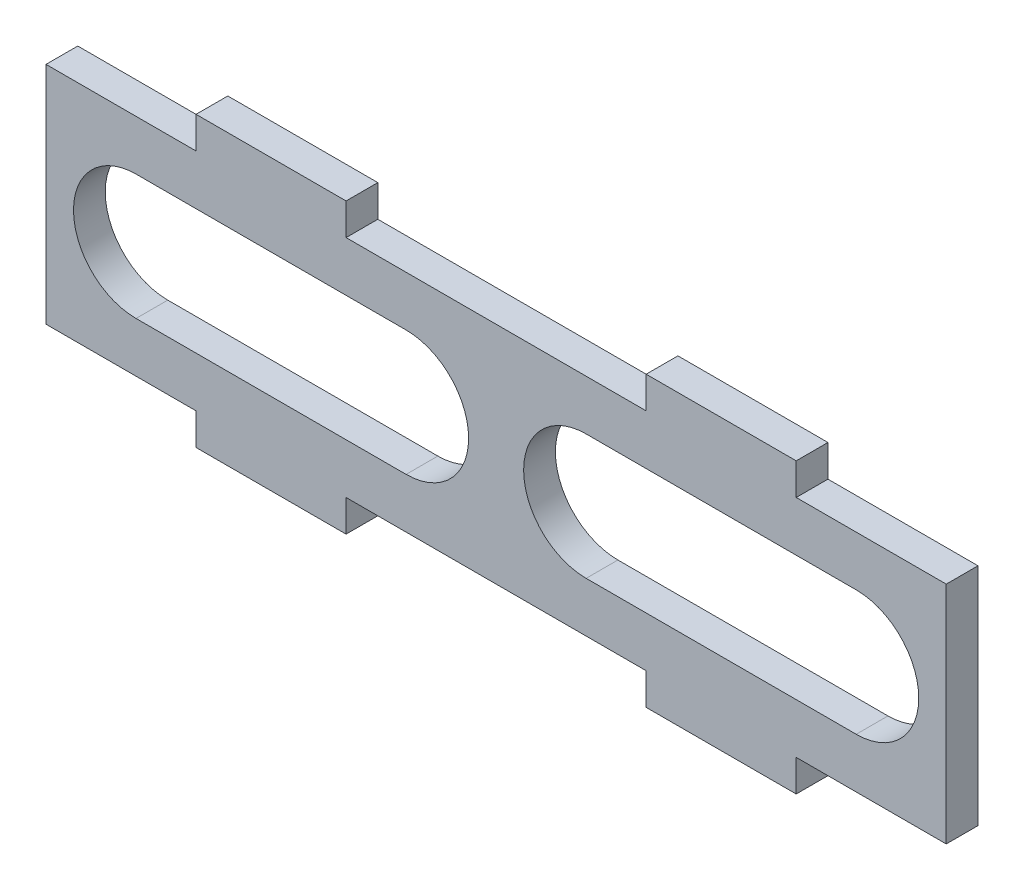
SolidWorks part; units mm, degrees
ref_plane "Plan de face" through (0, 0, 0) normal (0, 0, 1) x (1, 0, 0)
ref_plane "Plan de dessus" through (0, 0, 0) normal (0, 1, 0) x (1, 0, 0)
ref_plane "Plan de droite" through (0, 0, 0) normal (1, 0, 0) x (0, 0, -1)
sketch "Esquisse1" plane through (0, 0, 0) normal (0, 0, 1) x (1, 0, 0)
  line L1 (-90, 0) -> (90, 0)
  line L2 (-90, 0) -> (-90, 45)
  line L3 (-90, 45) -> (90, 45)
  line L4 (90, 0) -> (90, 45)
  point P4 (0, 0)
  dimension "D1" = 45
  dimension "D2" = 180
extrude "Boss.-Extru.1" add sketch "Esquisse1" along normal blind 6.35
sketch "Esquisse2" plane through (0, 0, 6.35) normal (0, 0, 1) x (1, 0, 0)
  line L0 (-90, 22.5) -> (90, 22.5) construction
  line L1 (-90, 45) -> (-90, 0) construction
  line L2 (90, 0) -> (90, 45) construction
  line L3 (-72, 22.5) -> (-18, 22.5) construction
  line L4 (-72, 35) -> (-18, 35)
  line L5 (-72, 10) -> (-18, 10)
  line L6 (0, 22.5) -> (0, 0) construction
  line L7 (0, 0) -> (-90, 0) construction
  line L8 (-45, 0) -> (-45, 22.5) construction
  line L9 (72, 22.5) -> (18, 22.5) construction
  line L10 (72, 35) -> (18, 35)
  line L11 (72, 10) -> (18, 10)
  arc A0 (-72, 35) -> (-72, 10) centre (-72, 22.5) ccw
  arc A1 (-18, 10) -> (-18, 35) centre (-18, 22.5) ccw
  arc A2 (72, 35) -> (72, 10) centre (72, 22.5) cw
  arc A3 (18, 10) -> (18, 35) centre (18, 22.5) cw
  point P8 (-45, 22.5)
  point P22 (45, 22.5)
  dimension "D1" = 18
  dimension "D2" = 25
extrude "Enlèv. mat.-Extru.1" cut sketch "Esquisse2" against normal up to next
sketch "Esquisse3" plane through (0, 0, 6.35) normal (0, 0, 1) x (1, 0, 0)
  line L0 (90, 45) -> (-90, 45) construction
  line L1 (-60, 45) -> (-30, 45)
  line L2 (-60, 45) -> (-60, 51.35)
  line L3 (-60, 51.35) -> (-30, 51.35)
  line L4 (-30, 45) -> (-30, 51.35)
  line L5 (-45, 45) -> (-45, 35) construction
  line L6 (-18, 35) -> (-72, 35) construction
  line L7 (0, 0) -> (0, 28.6567) construction
  line L8 (-90, 0) -> (90, 0) construction
  line L9 (-90, 22.5) -> (-48.7257, 22.5) construction
  line L10 (-90, 45) -> (-90, 0) construction
  line L11 (-60, -6.35) -> (-30, -6.35)
  line L12 (-30, 0) -> (-30, -6.35)
  line L13 (-60, 0) -> (-30, 0)
  line L14 (-60, 0) -> (-60, -6.35)
  line L15 (60, 0) -> (60, -6.35)
  line L16 (60, 0) -> (30, 0)
  line L17 (30, 0) -> (30, -6.35)
  line L18 (60, -6.35) -> (30, -6.35)
  line L19 (60, 51.35) -> (30, 51.35)
  line L20 (30, 45) -> (30, 51.35)
  line L21 (60, 45) -> (30, 45)
  line L22 (60, 45) -> (60, 51.35)
  dimension "D1" = 6.35
  dimension "D2" = 30
extrude "Boss.-Extru.2" add sketch "Esquisse3" against normal up to surface (6.35 mm away) up to face at (-45, 22.5, 0)
